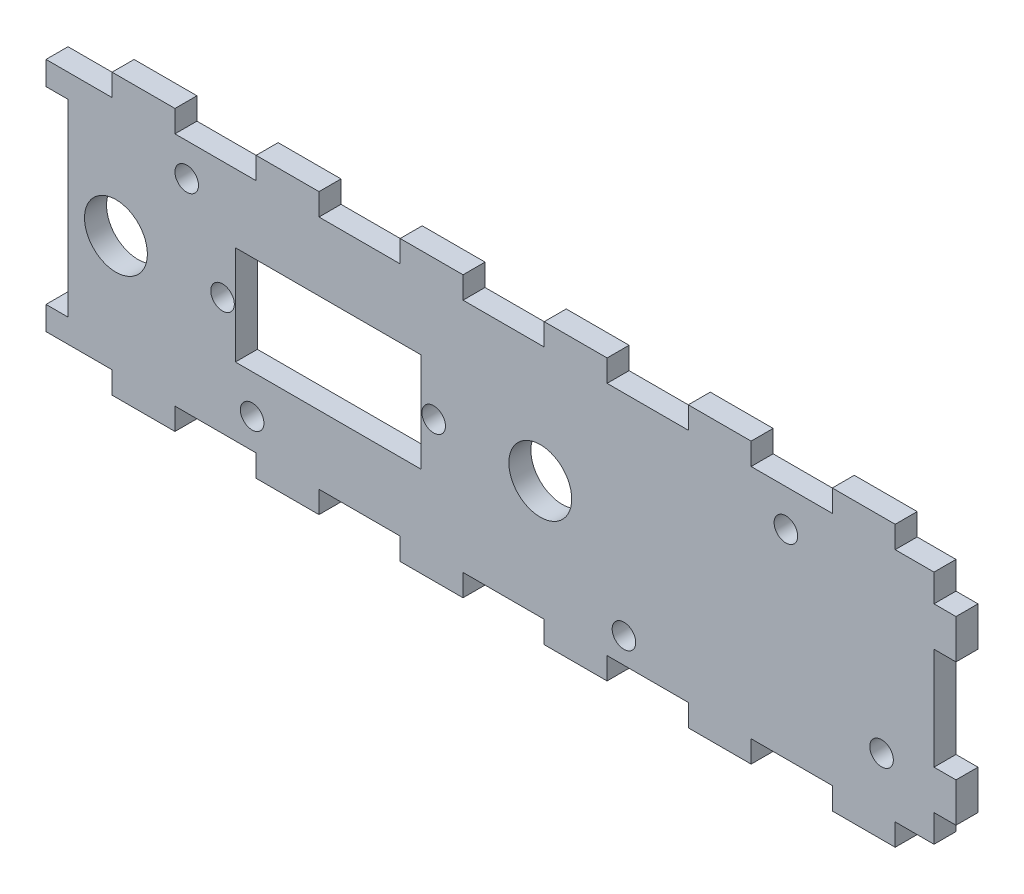
SolidWorks part; units mm, degrees
material "Фанера"
ref_plane "Front Plane" through (0, 0, 0) normal (0, 0, 1) x (1, 0, 0)
ref_plane "Top Plane" through (0, 0, 0) normal (0, 1, 0) x (1, 0, 0)
ref_plane "Right Plane" through (0, 0, 0) normal (1, 0, 0) x (0, 0, -1)
sketch "Эскиз1" plane through (0, 0, 0) normal (0, 0, 1) x (1, 0, 0)
  line L5 (0, -19.2753) -> (0, 20.3224) construction
  line L6 (-55.1, 15) -> (-49.49, 15)
  line L11 (-55.1, 12) -> (-55.1, 11.5)
  line L12 (-55.1, -15) -> (-49.49, -15)
  line L29 (55.1, 15) -> (55.1, 11.5)
  line L54 (-55.1, 15) -> (55.1, -15) construction
  line L60 (-55.1, -15) -> (55.1, 15) construction
  line L61 (-64.8201, 0) -> (75.1963, 0) construction
  line L62 (55.1, -5) -> (55.1, -6.5)
  line L67 (55.1, 5) -> (55.1, -5)
  line L68 (55.1, 6.5) -> (55.1, 5)
  line L69 (50.16, -15) -> (55.1, -15)
  line L71 (42.16, -15) -> (42.16, -17.8)
  line L72 (42.16, -17.8) -> (50.16, -17.8)
  line L74 (46.16, -15) -> (50.16, -17.8) construction
  line L75 (42.16, -17.8) -> (46.16, -15) construction
  line L76 (50.16, -15) -> (50.16, -17.8)
  line L77 (23.83, -17.8) -> (31.83, -17.8)
  line L78 (23.83, -15) -> (23.83, -17.8)
  line L79 (31.83, -15) -> (31.83, -17.8)
  line L80 (5.5, -17.8) -> (13.5, -17.8)
  line L81 (5.5, -15) -> (5.5, -17.8)
  line L82 (13.5, -15) -> (13.5, -17.8)
  line L83 (-12.83, -17.8) -> (-4.83, -17.8)
  line L84 (-12.83, -15) -> (-12.83, -17.8)
  line L85 (-4.83, -15) -> (-4.83, -17.8)
  line L86 (-31.16, -17.8) -> (-23.16, -17.8)
  line L87 (-31.16, -15) -> (-31.16, -17.8)
  line L88 (-23.16, -15) -> (-23.16, -17.8)
  line L89 (-49.49, -17.8) -> (-41.49, -17.8)
  line L90 (-49.49, -15) -> (-49.49, -17.8)
  line L91 (-41.49, -15) -> (-41.49, -17.8)
  line L92 (-41.49, -15) -> (-31.16, -15)
  line L93 (-23.16, -15) -> (-12.83, -15)
  line L94 (-4.83, -15) -> (5.5, -15)
  line L95 (13.5, -15) -> (23.83, -15)
  line L96 (31.83, -15) -> (42.16, -15)
  line L97 (50.16, 15) -> (50.16, 17.8)
  line L98 (42.16, 17.8) -> (50.16, 17.8)
  line L99 (42.16, 15) -> (42.16, 17.8)
  line L100 (31.83, 15) -> (31.83, 17.8)
  line L101 (23.83, 17.8) -> (31.83, 17.8)
  line L102 (23.83, 15) -> (23.83, 17.8)
  line L103 (13.5, 15) -> (13.5, 17.8)
  line L104 (5.5, 17.8) -> (13.5, 17.8)
  line L105 (5.5, 15) -> (5.5, 17.8)
  line L106 (-4.83, 15) -> (-4.83, 17.8)
  line L107 (-12.83, 17.8) -> (-4.83, 17.8)
  line L108 (-12.83, 15) -> (-12.83, 17.8)
  line L109 (-23.16, 15) -> (-23.16, 17.8)
  line L110 (-31.16, 17.8) -> (-23.16, 17.8)
  line L111 (-31.16, 15) -> (-31.16, 17.8)
  line L112 (-41.49, 15) -> (-41.49, 17.8)
  line L113 (-49.49, 15) -> (-49.49, 17.8)
  line L114 (-49.49, 17.8) -> (-41.49, 17.8)
  line L115 (-41.49, 15) -> (-31.16, 15)
  line L116 (-23.16, 15) -> (-12.83, 15)
  line L117 (-4.83, 15) -> (5.5, 15)
  line L118 (13.5, 15) -> (23.83, 15)
  line L119 (31.83, 15) -> (42.16, 15)
  line L120 (50.16, 15) -> (55.1, 15)
  line L124 (-55.1, -5) -> (-55.1, -6.5)
  line L125 (55.1, 11.5) -> (57.9, 11.5)
  line L127 (55.1, 6.5) -> (57.9, 6.5)
  line L128 (57.9, 11.5) -> (57.9, 6.5)
  line L129 (55.1, 9) -> (57.9, 6.5) construction
  line L130 (55.1, 9) -> (57.9, 11.5) construction
  line L131 (-55.1, 5) -> (-55.1, -5)
  line L132 (55.1, -6.5) -> (57.9, -6.5)
  line L133 (57.9, -11.5) -> (57.9, -6.5)
  line L134 (55.1, -11.5) -> (57.9, -11.5)
  line L135 (55.1, -11.5) -> (55.1, -15)
  line L142 (-55.1, 6.5) -> (-55.1, 5)
  line L143 (-55.1, -11.5) -> (-55.1, -12)
  line L144 (-55.1, -11.5) -> (-55.1, -6.5)
  line L145 (-55.1, 6.5) -> (-55.1, 11.5)
  line L146 (-55.1, -15) -> (-57.9, -15)
  line L147 (-57.9, -15) -> (-57.9, -12)
  line L148 (-57.9, -12) -> (-55.1, -12)
  line L149 (-57.9, 12) -> (-55.1, 12)
  line L150 (-55.1, 15) -> (-57.9, 15)
  line L151 (-57.9, 15) -> (-57.9, 12)
  circle A2 centre (5, 0) radius 4
  circle A3 centre (-49, 0) radius 4
  point P0 (0, 0)
  point P10 (57.6, 0)
  point P11 (55.1, 9)
  point P17 (46.16, -15)
  dimension "D11" = 8
  dimension "D12" = 50.1
  dimension "D13" = 54
  dimension "D1" = 30
  dimension "D2" = 110.2
  dimension "D3" = 5
  dimension "D4" = 6
  dimension "D5" = 2.8
  dimension "D6" = 4.94
  dimension "D8" = 4
  dimension "D9" = 2.8
  dimension "D10" = 6
  dimension "D7" = 8
  dimension "D14" = 2.5
  dimension "D15" = 3
  dimension "D16" = 2.8
extrude "Бобышка-Вытянуть1" add sketch "Эскиз1" along normal mid plane 2.8
sketch "Эскиз2" plane through (0, 0, -1.4) normal (0, 0, -1) x (-1, 0, 0)
  line L0 (10.2, 6.3) -> (33.8, 6.3) construction
  line L1 (10.2, 6.3) -> (33.8, 6.3)
  line L2 (10.2, 6.3) -> (10.2, -6.3) construction
  line L3 (10.2, 6.3) -> (10.2, -6.3)
  line L4 (10.2, -6.3) -> (33.8, -6.3) construction
  line L5 (33.8, 6.3) -> (33.8, -6.3) construction
  line L6 (10.2, -6.3) -> (33.8, -6.3)
  line L7 (33.8, 6.3) -> (33.8, -6.3)
  line L60 (-55.1, -15) -> (-50.16, -15)
  line L61 (-50.16, -15) -> (-50.16, -17.8)
  line L62 (-50.16, -17.8) -> (-42.16, -17.8)
  line L63 (-42.16, -17.8) -> (-42.16, -15)
  line L64 (-42.16, -15) -> (-31.83, -15)
  line L65 (-31.83, -15) -> (-31.83, -17.8)
  line L66 (-31.83, -17.8) -> (-23.83, -17.8)
  line L67 (-23.83, -17.8) -> (-23.83, -15)
  line L68 (-23.83, -15) -> (-13.5, -15)
  line L69 (-13.5, -15) -> (-13.5, -17.8)
  line L70 (-13.5, -17.8) -> (-5.5, -17.8)
  line L71 (-5.5, -17.8) -> (-5.5, -15)
  line L72 (-5.5, -15) -> (4.83, -15)
  line L73 (4.83, -15) -> (4.83, -17.8)
  line L74 (4.83, -17.8) -> (12.83, -17.8)
  line L75 (12.83, -17.8) -> (12.83, -15)
  line L76 (12.83, -15) -> (23.16, -15)
  line L77 (23.16, -15) -> (23.16, -17.8)
  line L78 (23.16, -17.8) -> (31.16, -17.8)
  line L79 (31.16, -17.8) -> (31.16, -15)
  line L80 (31.16, -15) -> (41.49, -15)
  line L81 (41.49, -15) -> (41.49, -17.8)
  line L82 (41.49, -17.8) -> (49.49, -17.8)
  line L83 (49.49, -17.8) -> (49.49, -15)
  line L84 (49.49, -15) -> (57.9, -15)
  line L85 (55.1, -12) -> (55.1, 12)
  line L86 (-55.1, -11.5) -> (-55.1, -15)
  line L87 (-55.1, -11.5) -> (-55.1, -15)
  line L88 (57.9, -15) -> (57.9, -12)
  line L89 (57.9, -15) -> (57.9, -12)
  line L90 (57.9, 15) -> (49.49, 15)
  line L91 (49.49, 15) -> (49.49, 17.8)
  line L92 (49.49, 17.8) -> (41.49, 17.8)
  line L93 (41.49, 17.8) -> (41.49, 15)
  line L94 (41.49, 15) -> (31.16, 15)
  line L95 (31.16, 15) -> (31.16, 17.8)
  line L96 (31.16, 17.8) -> (23.16, 17.8)
  line L97 (23.16, 17.8) -> (23.16, 15)
  line L98 (23.16, 15) -> (12.83, 15)
  line L99 (12.83, 15) -> (12.83, 17.8)
  line L100 (12.83, 17.8) -> (4.83, 17.8)
  line L101 (4.83, 17.8) -> (4.83, 15)
  line L102 (4.83, 15) -> (-5.5, 15)
  line L103 (-5.5, 15) -> (-5.5, 17.8)
  line L104 (-5.5, 17.8) -> (-13.5, 17.8)
  line L105 (-13.5, 17.8) -> (-13.5, 15)
  line L106 (-13.5, 15) -> (-23.83, 15)
  line L107 (-23.83, 15) -> (-23.83, 17.8)
  line L108 (-23.83, 17.8) -> (-31.83, 17.8)
  line L109 (-31.83, 17.8) -> (-31.83, 15)
  line L110 (-31.83, 15) -> (-42.16, 15)
  line L111 (-42.16, 15) -> (-42.16, 17.8)
  line L112 (-42.16, 17.8) -> (-50.16, 17.8)
  line L113 (-50.16, 17.8) -> (-50.16, 15)
  line L114 (-50.16, 15) -> (-55.1, 15)
  line L115 (-55.1, 15) -> (-55.1, 11.5)
  line L116 (-55.1, 6.5) -> (-55.1, -6.5)
  line L118 (57.9, -12) -> (55.1, -12)
  line L120 (-55.1, -15) -> (-50.16, -15)
  line L121 (-50.16, -15) -> (-50.16, -17.8)
  line L122 (-50.16, -17.8) -> (-42.16, -17.8)
  line L123 (-42.16, -17.8) -> (-42.16, -15)
  line L124 (-42.16, -15) -> (-31.83, -15)
  line L125 (-31.83, -15) -> (-31.83, -17.8)
  line L126 (-31.83, -17.8) -> (-23.83, -17.8)
  line L127 (-23.83, -17.8) -> (-23.83, -15)
  line L128 (-23.83, -15) -> (-13.5, -15)
  line L129 (-13.5, -15) -> (-13.5, -17.8)
  line L130 (-13.5, -17.8) -> (-5.5, -17.8)
  line L131 (-5.5, -17.8) -> (-5.5, -15)
  line L132 (-5.5, -15) -> (4.83, -15)
  line L133 (4.83, -15) -> (4.83, -17.8)
  line L134 (4.83, -17.8) -> (12.83, -17.8)
  line L135 (12.83, -17.8) -> (12.83, -15)
  line L136 (12.83, -15) -> (23.16, -15)
  line L137 (23.16, -15) -> (23.16, -17.8)
  line L138 (23.16, -17.8) -> (31.16, -17.8)
  line L139 (31.16, -17.8) -> (31.16, -15)
  line L140 (31.16, -15) -> (41.49, -15)
  line L141 (41.49, -15) -> (41.49, -17.8)
  line L142 (41.49, -17.8) -> (49.49, -17.8)
  line L143 (49.49, -17.8) -> (49.49, -15)
  line L144 (49.49, -15) -> (57.9, -15)
  line L145 (55.1, -12) -> (55.1, 12)
  line L150 (57.9, 15) -> (49.49, 15)
  line L151 (49.49, 15) -> (49.49, 17.8)
  line L152 (49.49, 17.8) -> (41.49, 17.8)
  line L153 (41.49, 17.8) -> (41.49, 15)
  line L154 (41.49, 15) -> (31.16, 15)
  line L155 (31.16, 15) -> (31.16, 17.8)
  line L156 (31.16, 17.8) -> (23.16, 17.8)
  line L157 (23.16, 17.8) -> (23.16, 15)
  line L158 (23.16, 15) -> (12.83, 15)
  line L159 (12.83, 15) -> (12.83, 17.8)
  line L160 (12.83, 17.8) -> (4.83, 17.8)
  line L161 (4.83, 17.8) -> (4.83, 15)
  line L162 (4.83, 15) -> (-5.5, 15)
  line L163 (-5.5, 15) -> (-5.5, 17.8)
  line L164 (-5.5, 17.8) -> (-13.5, 17.8)
  line L165 (-13.5, 17.8) -> (-13.5, 15)
  line L166 (-13.5, 15) -> (-23.83, 15)
  line L167 (-23.83, 15) -> (-23.83, 17.8)
  line L168 (-23.83, 17.8) -> (-31.83, 17.8)
  line L169 (-31.83, 17.8) -> (-31.83, 15)
  line L170 (-31.83, 15) -> (-42.16, 15)
  line L171 (-42.16, 15) -> (-42.16, 17.8)
  line L172 (-42.16, 17.8) -> (-50.16, 17.8)
  line L173 (-50.16, 17.8) -> (-50.16, 15)
  line L174 (-50.16, 15) -> (-55.1, 15)
  line L175 (-55.1, 15) -> (-55.1, 11.5)
  line L176 (-55.1, 6.5) -> (-55.1, -6.5)
  line L192 (57.9, -12) -> (55.1, -12)
  line L193 (55.1, 12) -> (57.9, 12)
  line L194 (55.1, 12) -> (57.9, 12)
  line L195 (57.9, 12) -> (57.9, 15)
  line L196 (57.9, 12) -> (57.9, 15)
  line L206 (-55.1, 11.5) -> (-57.9, 11.5)
  line L207 (-55.1, 11.5) -> (-57.9, 11.5)
  line L208 (-57.9, 11.5) -> (-57.9, 6.5)
  line L209 (-57.9, 11.5) -> (-57.9, 6.5)
  line L210 (-57.9, 6.5) -> (-55.1, 6.5)
  line L211 (-57.9, 6.5) -> (-55.1, 6.5)
  line L212 (-55.1, -6.5) -> (-57.9, -6.5)
  line L213 (-55.1, -6.5) -> (-57.9, -6.5)
  line L214 (-57.9, -6.5) -> (-57.9, -11.5)
  line L215 (-57.9, -6.5) -> (-57.9, -11.5)
  line L216 (-57.9, -11.5) -> (-55.1, -11.5)
  line L217 (-57.9, -11.5) -> (-55.1, -11.5)
  circle A0 centre (35.435, 0) radius 1.5 construction
  circle A1 centre (8.565, 0) radius 1.5 construction
  circle A2 centre (35.435, 0) radius 1.5
  circle A3 centre (8.565, 0) radius 1.5
  dimension "D1" = 0
extrude "Вырез-Вытянуть1" cut sketch "Эскиз2" against normal through all both and the other way through all contours L7 L1 L3 L6 | A3 | A2
sketch "Эскиз3" plane through (0, 0, -1.4) normal (0, 0, -1) x (-1, 0, 0)
  circle A0 centre (31.6679, -11.2285) radius 1.5 construction
  circle A1 centre (-48.4294, -8.3) radius 1.5 construction
  circle A2 centre (-15.6482, -11.7437) radius 1.5 construction
  circle A3 centre (39.9924, 10.8146) radius 1.5 construction
  circle A4 centre (-36.2531, 10.2844) radius 1.5 construction
  circle A5 centre (31.6679, -11.2285) radius 1.5
  circle A6 centre (-48.4294, -8.3) radius 1.5
  circle A7 centre (-15.6482, -11.7437) radius 1.5
  circle A8 centre (39.9924, 10.8146) radius 1.5
  circle A9 centre (-36.2531, 10.2844) radius 1.5
extrude "Вырез-Вытянуть2" cut sketch "Эскиз3" against normal through all both and the other way through all
